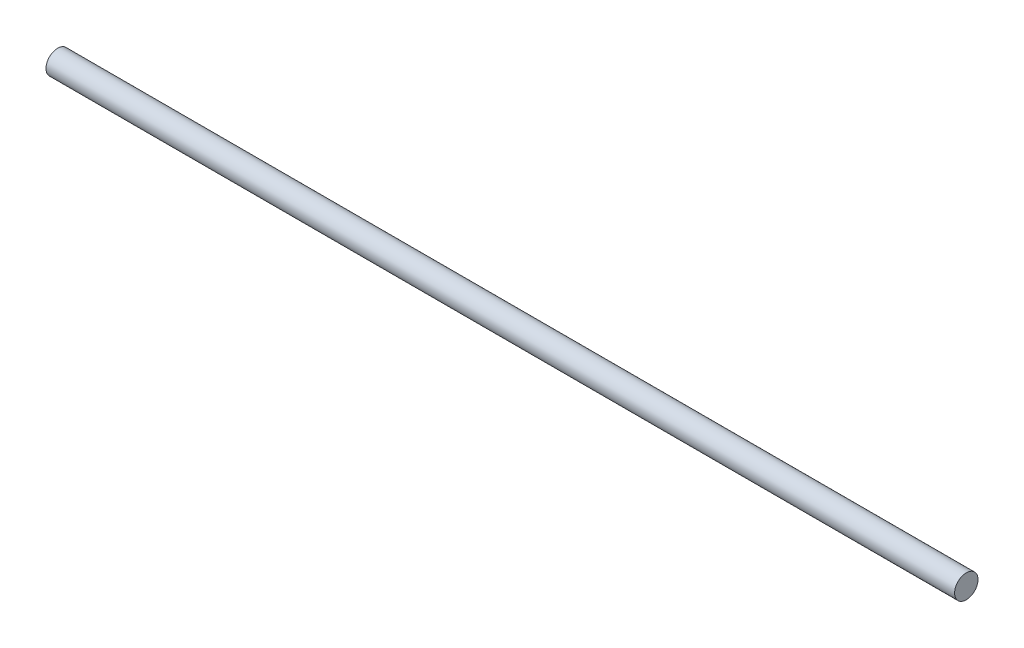
SolidWorks part; units mm, degrees
ref_plane "Ön Düzlem" through (0, 0, 0) normal (0, 0, 1) x (1, 0, 0)
ref_plane "Üst Düzlem" through (0, 0, 0) normal (0, 1, 0) x (1, 0, 0)
ref_plane "Sağ Düzlem" through (0, 0, 0) normal (1, 0, 0) x (0, 0, -1)
sketch "Sketch1" plane through (0, 0, 0) normal (0, 0, 1) x (1, 0, 0)
  line L2 (4, 4) -> (198, 4)
ref_plane "Plane2" through (198, 0, 0) normal (1, 0, 0) x (0, 0, -1)
sketch "Sketch7" plane through (198, 0, 0) normal (1, 0, 0) x (0, 0, -1)
  circle A0 centre (0, 4) radius 2.5
sweep "Sweep1" add profiles "Sketch7" path "Sketch1"
